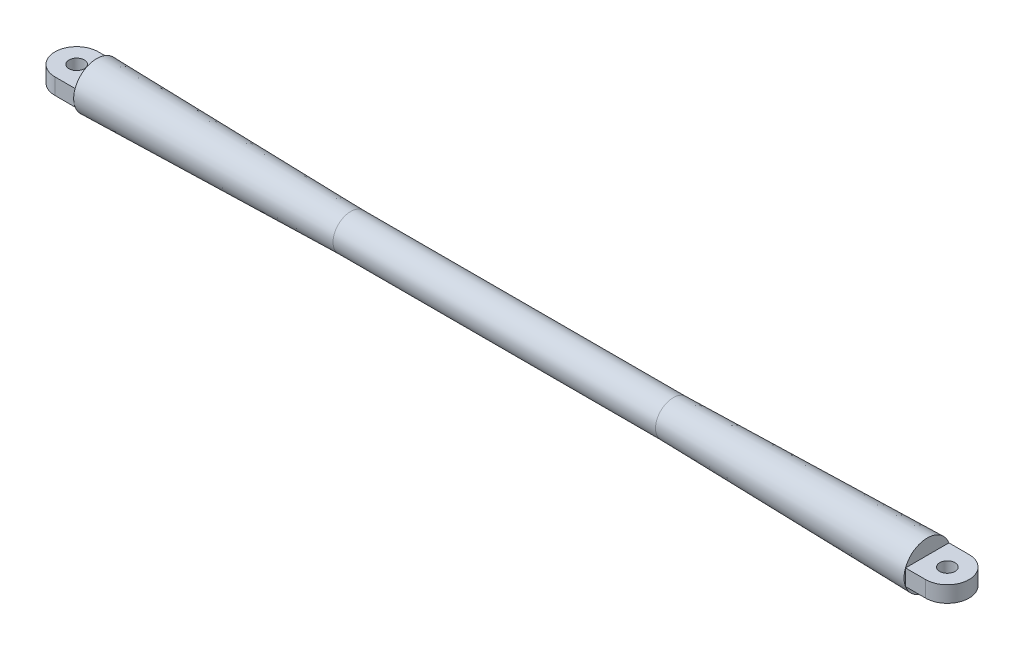
SolidWorks part; units mm, degrees
ref_plane "Front Plane" through (0, 0, 0) normal (0, 0, 1) x (1, 0, 0)
ref_plane "Top Plane" through (0, 0, 0) normal (0, 1, 0) x (1, 0, 0)
ref_plane "Right Plane" through (0, 0, 0) normal (1, 0, 0) x (0, 0, -1)
sketch "Sketch1" plane through (0, 0, 0) normal (0, 0, 1) x (1, 0, 0)
  line L0 (0, 0) -> (575, 0)
  line L1 (575, 0) -> (575, 30)
  line L2 (575, 30) -> (200, 22)
  line L3 (200, 22) -> (0, 22)
  line L4 (0, 22) -> (0, 0)
  dimension "D1" = 22
  dimension "D2" = 30
  dimension "D3" = 575
  dimension "D4" = 200
revolve "Revolve1" add sketch "Sketch1" angle 360 about L0
sketch "Sketch2" plane through (0, 0, 0) normal (0, 0, 1) x (1, 0, 0)
  line L0 (575, 0) -> (634.7249, 0) construction
  line L1 (515, 50.2037) -> (596.2199, 50.2037)
  line L2 (515, 50.2037) -> (515, 10)
  line L3 (515, 10) -> (596.2199, 10)
  line L4 (596.2199, 50.2037) -> (596.2199, 10)
  line L5 (575, -30) -> (575, 30) construction
  line L6 (515, -10) -> (596.2199, -10)
  line L7 (515, -50.2037) -> (515, -10)
  line L8 (515, -50.2037) -> (596.2199, -50.2037)
  line L9 (596.2199, -50.2037) -> (596.2199, -10)
  dimension "D1" = 10
  dimension "D2" = 60
extrude "Cut-Extrude1" cut sketch "Sketch2" against normal mid plane 70
sketch "Sketch3" plane through (0, 10, 0) normal (0, 1, 0) x (1, 0, 0)
  line L0 (515, 26.9228) -> (540, 26.9228)
  line L1 (540, -26.9228) -> (515, -26.9228)
  line L2 (515, 26.9228) -> (515, 35.0997)
  line L3 (515, 35.0997) -> (579.5288, 35.0997)
  line L4 (579.5288, 35.0997) -> (579.5288, -33.4261)
  line L5 (579.5288, -33.4261) -> (515, -33.4261)
  line L6 (515, -33.4261) -> (515, -26.9228)
  arc A0 (540, 26.9228) -> (540, -26.9228) centre (540, 0) cw
  dimension "D1" = 25
extrude "Cut-Extrude2" cut sketch "Sketch3" against normal mid plane 70
sketch "Sketch4" plane through (0, 10, 0) normal (0, 1, 0) x (1, 0, 0)
  circle A1 centre (540, 0) radius 9.5
  dimension "D1" = 19
extrude "Cut-Extrude3" cut sketch "Sketch4" against normal through all
mirror "Mirror1" about plane through (0, 0, 0) normal (1, 0, 0) of "Revolve1", "Cut-Extrude1", "Cut-Extrude2", "Cut-Extrude3"
